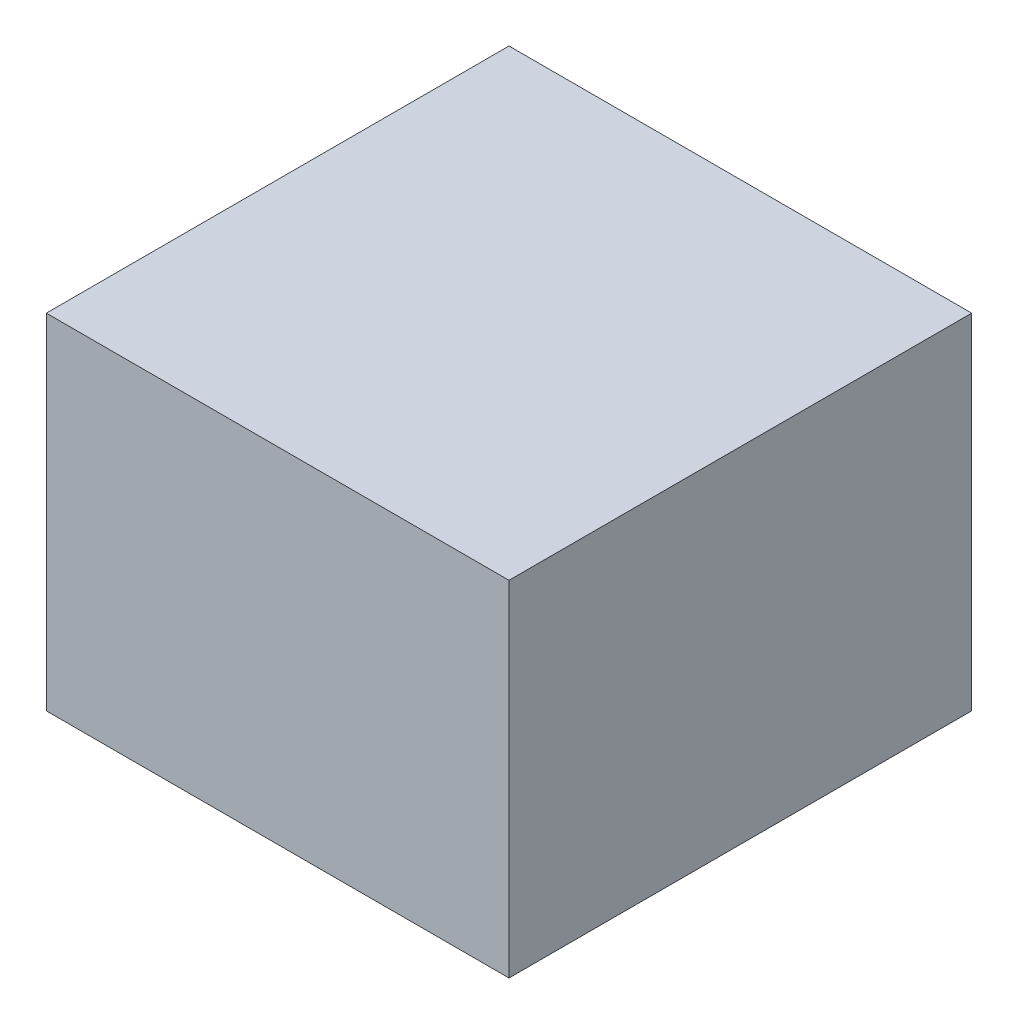
SolidWorks part; units mm, degrees
ref_plane "Front Plane" through (0, 0, 0) normal (0, 0, 1) x (1, 0, 0)
ref_plane "Top Plane" through (0, 0, 0) normal (0, 1, 0) x (1, 0, 0)
ref_plane "Right Plane" through (0, 0, 0) normal (1, 0, 0) x (0, 0, -1)
sketch "Sketch1" plane through (0, 0, 0) normal (0, 1, 0) x (1, 0, 0)
  line L1 (0, 0) -> (45, 0)
  line L2 (0, 0) -> (0, 45)
  line L3 (0, 45) -> (45, 45)
  line L4 (45, 0) -> (45, 45)
  dimension "D1" = 45
  dimension "D2" = 45
extrude "Boss-Extrude1" add sketch "Sketch1" along normal blind 33.5
